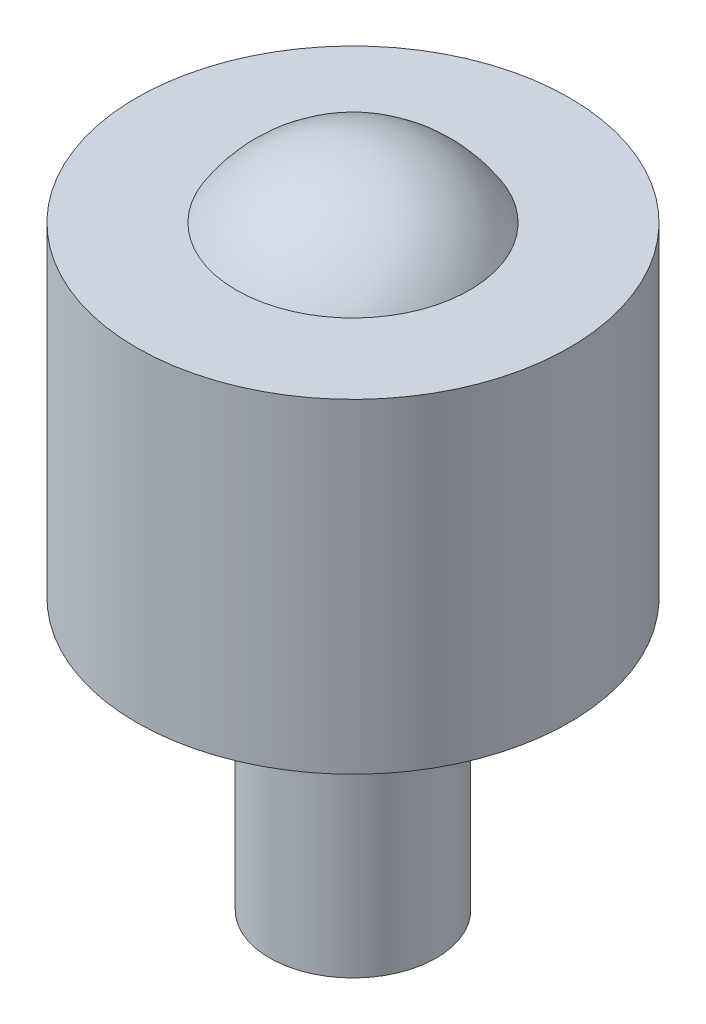
SolidWorks part; units mm, degrees
ref_plane "Plan de face" through (0, 0, 0) normal (0, 0, 1) x (1, 0, 0)
ref_plane "Plan de dessus" through (0, 0, 0) normal (0, 1, 0) x (1, 0, 0)
ref_plane "Plan de droite" through (0, 0, 0) normal (1, 0, 0) x (0, 0, -1)
sketch "Esquisse1" plane through (0, 0, 0) normal (0, 1, 0) x (1, 0, 0)
  circle A0 centre (0, 0) radius 10
  dimension "D1" = 20
extrude "Boss.-Extru.1" add sketch "Esquisse1" along normal blind 15
sketch "Esquisse2" plane through (0, 0, 0) normal (1, 0, 0) x (0, 0, -1)
  line L0 (0, 0) -> (0, 18) construction
  line L1 (10, 15) -> (-10, 15) construction
  line L2 (0, 5.3) -> (0, 18)
  arc A1 (0, 18) -> (0, 5.3) centre (0, 11.65) ccw
  dimension "D1" = 6.35
  dimension "D2" = 3
revolve "Révolution6" add sketch "Esquisse2" angle 360 about L0
sketch "Esquisse3" plane through (0, 0, 0) normal (0, -1, 0) x (1, 0, 0)
  circle A0 centre (0, 0) radius 3.85
  dimension "D1" = 7.7
extrude "Boss.-Extru.2" add sketch "Esquisse3" along normal blind 12.5
ref_plane "Plan1" through (0, 18, 0) normal (0, 1, 0) x (1, 0, 0)
